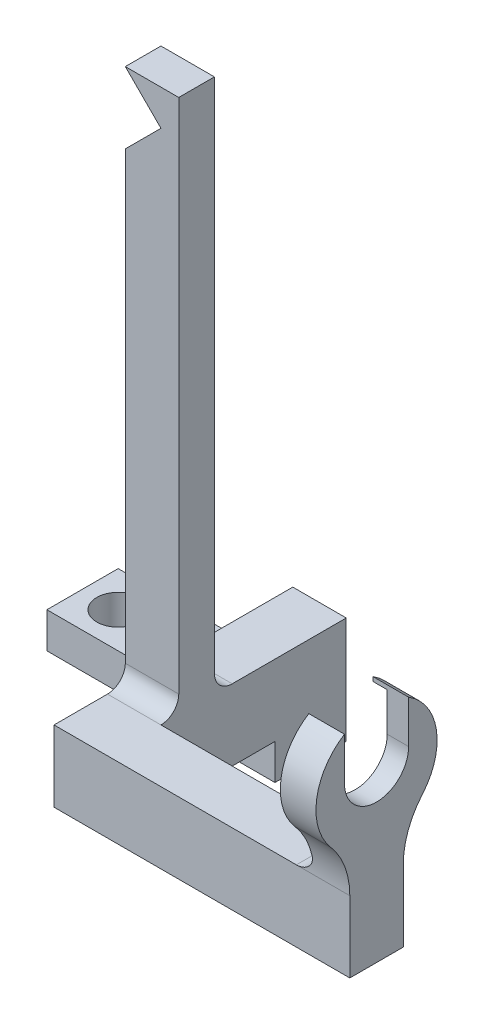
SolidWorks part; units mm, degrees
ref_plane "Front Plane" through (0, 0, 0) normal (0, 0, 1) x (1, 0, 0)
ref_plane "Top Plane" through (0, 0, 0) normal (0, 1, 0) x (1, 0, 0)
ref_plane "Right Plane" through (0, 0, 0) normal (1, 0, 0) x (0, 0, -1)
sketch "Sketch2" plane through (0, 0, 0) normal (0, 1, 0) x (1, 0, 0)
  line L0 (-50.3379, 0) -> (50.3379, 0) construction
  line L1 (-5, -5) -> (-5, 5)
  line L2 (-5, 5) -> (17, 5)
  line L3 (17, 5) -> (17, -5)
  line L4 (17, -5) -> (-5, -5)
  circle A0 centre (0, 0) radius 3
  circle A1 centre (12, 0) radius 3
  point P9 (-5, 0)
  dimension "D1" = 6
  dimension "D2" = 12
  dimension "D3" = 10
  dimension "D4" = 22
  dimension "D5" = 5
extrude "Boss-Extrude1" add sketch "Sketch2" along normal blind 5
sketch "Sketch3" plane through (0, 0, 5) normal (0, 0, 1) x (1, 0, 0)
  line L0 (17, 5) -> (27, 5)
  line L1 (27, 5) -> (27, 0)
  line L2 (27, 0) -> (17, 0)
  line L3 (55, 0) -> (-55, 0) construction
  line L4 (17, 5) -> (17, 0) construction
  line L5 (17, 0) -> (17, 5)
  dimension "D1" = 10
extrude "Boss-Extrude2" add sketch "Sketch3" against normal up to vertex (10 mm away) up to point (17, 5, -5)
sketch "Sketch4" plane through (0, 5, 0) normal (0, 1, 0) x (1, 0, 0)
  line L0 (27, 5) -> (27, -5)
  line L1 (27, 5) -> (27, -5) construction
  line L2 (27, 5) -> (-5, 5) construction
  line L4 (19.5, -7.5) -> (19.5, 5)
  line L5 (19.5, 5) -> (27, 5)
  line L8 (19.5, -18.5) -> (27, -18.5)
  line L11 (27, -7.5) -> (27, -18.5)
  line L12 (-5, -5) -> (27, -5) construction
  line L13 (19.5, -7.5) -> (19.5, -18.5)
  line L14 (27, -7.5) -> (27, -5)
  circle A4 centre (12, 0) radius 3 construction
  dimension "D2" = 7.5
  dimension "D3" = 11
  dimension "D4" = 18.5
extrude "Boss-Extrude3" add sketch "Sketch4" along normal blind 10
sketch "Sketch5" plane through (0, 15, 0) normal (0, 1, 0) x (1, 0, 0)
  line L0 (27, -18.5) -> (27, -13.5)
  line L2 (27, -13.5) -> (19.5, -13.5)
  line L4 (19.5, -13.5) -> (19.5, -18.5)
  line L5 (19.5, -18.5) -> (27, -18.5)
  dimension "D1" = 5
extrude "Boss-Extrude4" add sketch "Sketch5" along normal blind 75
sketch "Sketch6" plane through (0, 0, 18.5) normal (0, 0, 1) x (1, 0, 0)
  line L0 (19.5, 90) -> (24.5, 85)
  line L1 (24.5, 85) -> (19.5, 80)
  line L2 (19.5, 90) -> (19.5, 5) construction
  line L3 (19.5, 80) -> (19.5, 90)
  dimension "D1" = 5
extrude "Cut-Extrude1" cut sketch "Sketch6" against normal up to next
sketch "Sketch7" plane through (0, 15, 0) normal (0, 1, 0) x (1, 0, 0)
  line L0 (19.5, 5) -> (19.5, -28.5)
  line L4 (27, -21) -> (27, 5)
  line L5 (27, 5) -> (19.5, 5)
  line L11 (36.2588, -2.8088) -> (36.2588, 22.8824) construction
  line L12 (36.2588, -2.8088) -> (36.2588, -28.5) construction
  line L13 (19.5, -28.5) -> (56, -28.5)
  line L14 (56, -28.5) -> (56, -21)
  line L15 (56, -21) -> (27, -21)
  line L18 (19.5, -18.5) -> (27, -18.5) construction
  dimension "D1" = 29
  dimension "D2" = 7.5
  dimension "D3" = 2.5
extrude "Boss-Extrude5" add sketch "Sketch7" against normal blind 10
sketch "Sketch13" plane through (0, 0, 21) normal (0, 0, -1) x (-1, 0, 0)
  line L0 (-56, 5) -> (-56, 15)
  line L1 (-56, 15) -> (-61, 15)
  line L2 (-61, 15) -> (-61, 5)
  line L3 (-27, 5) -> (-56, 5) construction
  line L4 (-61, 5) -> (-56, 5)
  dimension "D1" = 5
  dimension "D2" = 10
extrude "Boss-Extrude6" add sketch "Sketch13" against normal up to vertex (7.5 mm away)
sketch "Sketch14" plane through (61, 0, 0) normal (1, 0, 0) x (0, 0, -1)
  line L0 (-29.25, 35) -> (-20.25, 35)
  line L1 (-28.5, 15) -> (-21, 15) construction
  line L5 (-24.75, 21) -> (-24.75, 27.7889) construction
  line L6 (-28.5, 15) -> (-21, 15)
  arc A1 (-29.25, 35) -> (-31.1891, 22.2403) centre (-24.75, 27.7889) ccw
  arc A2 (-28.5, 15) -> (-31.1891, 22.2403) centre (-39.5914, 15) ccw
  arc A3 (-21, 15) -> (-18.3109, 22.2403) centre (-9.9086, 15) cw
  arc A4 (-18.3109, 22.2403) -> (-20.25, 35) centre (-24.75, 27.7889) ccw
  dimension "D1" = 8.5
  dimension "D2" = 9
  dimension "D3" = 20
extrude "Boss-Extrude7" add sketch "Sketch14" against normal blind 5
sketch "Sketch15" plane through (61, 0, 0) normal (1, 0, 0) x (0, 0, -1)
  line L0 (-29.25, 35) -> (-29.25, 29)
  line L1 (-20.25, 35) -> (-20.25, 29)
  line L3 (-29.25, 35) -> (-20.25, 35)
  arc A0 (-29.25, 29) -> (-20.25, 29) centre (-24.75, 29) ccw
  point P22 (-24.75, 35)
  dimension "D1" = 6
extrude "Cut-Extrude5" cut sketch "Sketch15" against normal up to next
sketch "Sketch16" plane through (56, 0, 0) normal (1, 0, 0) x (0, 0, -1)
  circle A2 centre (-24.75, 27.7889) radius 8
  arc A3 (-29.25, 35) -> (-31.1891, 22.2403) centre (-24.75, 27.7889) ccw construction
  dimension "D1" = 0.5
extrude "Cut-Extrude6" cut sketch "Sketch16" along normal blind 2
ref_plane "Plane1" through (56, 15, 28.5) normal (0, 0, -1) x (-1, 0, 0)
sketch "Sketch17" plane through (56, 15, 28.5) normal (0, 0, -1) x (-1, 0, 0)
  line L0 (0, 0) -> (0, 2.5)
  line L1 (36.5, 0) -> (0, 0) construction
  line L2 (0, 0) -> (2.5, 0)
  arc A0 (0, 2.5) -> (2.5, 0) centre (2.5, 2.5) ccw
  dimension "D1" = 2.5
extrude "Boss-Extrude8" add sketch "Sketch17" along normal up to surface and the other way up to surface up to face at (58.5, 18.7409, 19.9807) other way up to face at (58.5, 18.7409, 29.5193)
sketch "Sketch18" plane through (27, 0, 0) normal (1, 0, 0) x (0, 0, -1)
  line L0 (-13.5, 15) -> (-13.5, 17.5)
  line L1 (-13.5, 90) -> (-13.5, 15) construction
  line L2 (-13.5, 15) -> (-11, 15)
  line L3 (-13.5, 15) -> (5, 15) construction
  line L4 (-18.5, 15) -> (-18.5, 17.5)
  line L5 (-18.5, 90) -> (-18.5, 15) construction
  line L6 (-18.5, 15) -> (-21, 15)
  line L7 (-21, 15) -> (-18.5, 15) construction
  arc A0 (-18.5, 17.5) -> (-21, 15) centre (-21, 17.5) cw
  arc A1 (-13.5, 17.5) -> (-11, 15) centre (-11, 17.5) ccw
  dimension "D1" = 2.5
extrude "Boss-Extrude9" add sketch "Sketch18" against normal up to surface (7.5 mm away) up to face at (19.5, 26.1111, 12.8889)
sketch "Sketch19" plane through (0, 0, -5) normal (0, 0, -1) x (-1, 0, 0)
  line L0 (-19.5, 5) -> (-19.5, 9.5)
  line L1 (-19.5, 5) -> (-15, 5)
  line L2 (-19.5, 5) -> (5, 5) construction
  line L4 (-9, 5) -> (-15, 5) construction
  line L5 (-9, 5) -> (-15, 5) construction
  arc A0 (-19.5, 9.5) -> (-15, 5) centre (-15, 9.5) ccw
  point P8 (-27.5, 8.9072)
  point P11 (0, 0)
extrude "Boss-Extrude10" add sketch "Sketch19" against normal up to vertex
